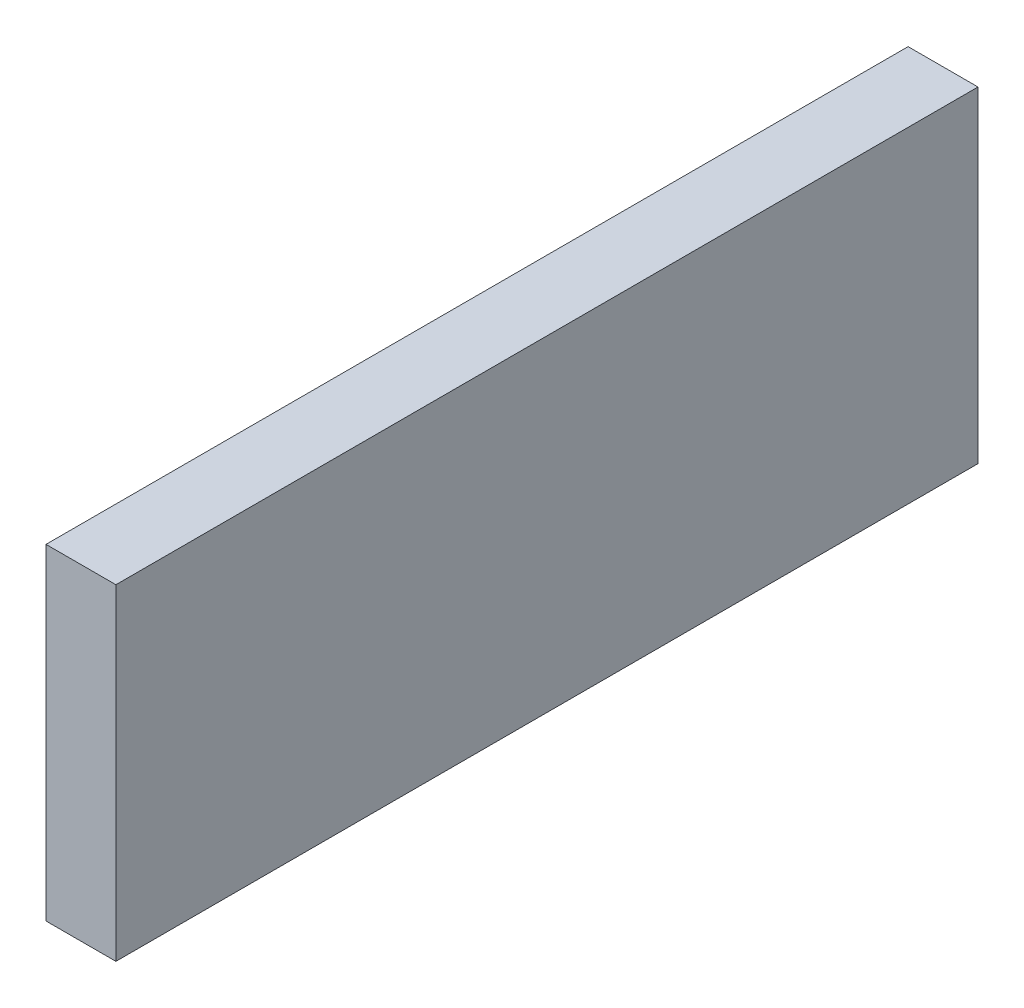
SolidWorks part; units mm, degrees
ref_plane "Front Plane" through (0, 0, 0) normal (0, 0, 1) x (1, 0, 0)
ref_plane "Top Plane" through (0, 0, 0) normal (0, 1, 0) x (1, 0, 0)
ref_plane "Right Plane" through (0, 0, 0) normal (1, 0, 0) x (0, 0, -1)
sketch "Sketch1" plane through (0, 0, 0) normal (0, 1, 0) x (1, 0, 0)
  line L1 (0, 0) -> (3, 0)
  line L6 (0, 0) -> (0, 37)
  line L7 (0, 37) -> (3, 37)
  line L8 (3, 0) -> (3, 37)
  dimension "D1" = 37
  dimension "D2" = 3
extrude "Boss-Extrude1" add sketch "Sketch1" along normal blind 14
